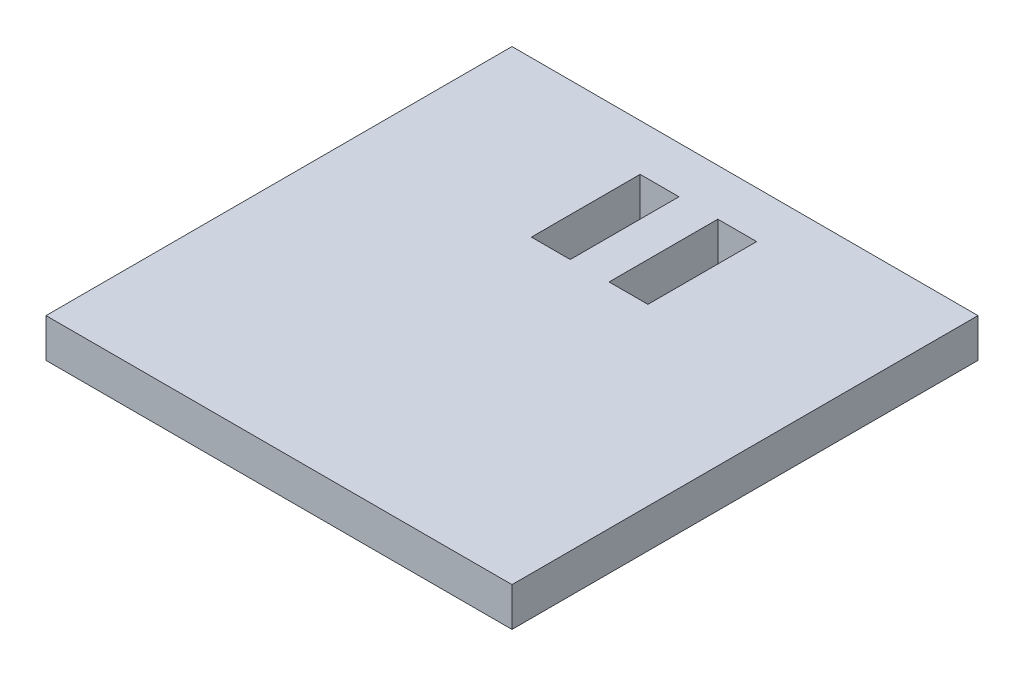
SolidWorks part; units mm, degrees
ref_plane "Front Plane" through (0, 0, 0) normal (0, 0, 1) x (1, 0, 0)
ref_plane "Top Plane" through (0, 0, 0) normal (0, 1, 0) x (1, 0, 0)
ref_plane "Right Plane" through (0, 0, 0) normal (1, 0, 0) x (0, 0, -1)
sketch "Sketch1" plane through (0, 0, 0) normal (0, 1, 0) x (1, 0, 0)
  line L1 (0, 0) -> (38.1, 0)
  line L2 (0, 0) -> (0, 38.1)
  line L3 (0, 38.1) -> (38.1, 38.1)
  line L4 (38.1, 0) -> (38.1, 38.1)
  line L5 (14.2875, 34.29) -> (17.4625, 34.29)
  line L6 (14.2875, 34.29) -> (14.2875, 25.4)
  line L7 (14.2875, 25.4) -> (17.4625, 25.4)
  line L8 (17.4625, 34.29) -> (17.4625, 25.4)
  line L9 (20.6375, 34.29) -> (23.8125, 34.29)
  line L10 (20.6375, 34.29) -> (20.6375, 25.4)
  line L11 (20.6375, 25.4) -> (23.8125, 25.4)
  line L12 (23.8125, 34.29) -> (23.8125, 25.4)
  point P9 (14.2875, 29.845)
  dimension "D1" = 38.1
  dimension "D2" = 38.1
  dimension "D3" = 8.89
  dimension "D4" = 3.175
  dimension "D5" = 14.2875
  dimension "D6" = 3.81
  dimension "D7" = 8.89
  dimension "D8" = 3.175
  dimension "D9" = 3.81
  dimension "D10" = 14.2875
extrude "Boss-Extrude1" add sketch "Sketch1" along normal blind 3.175
